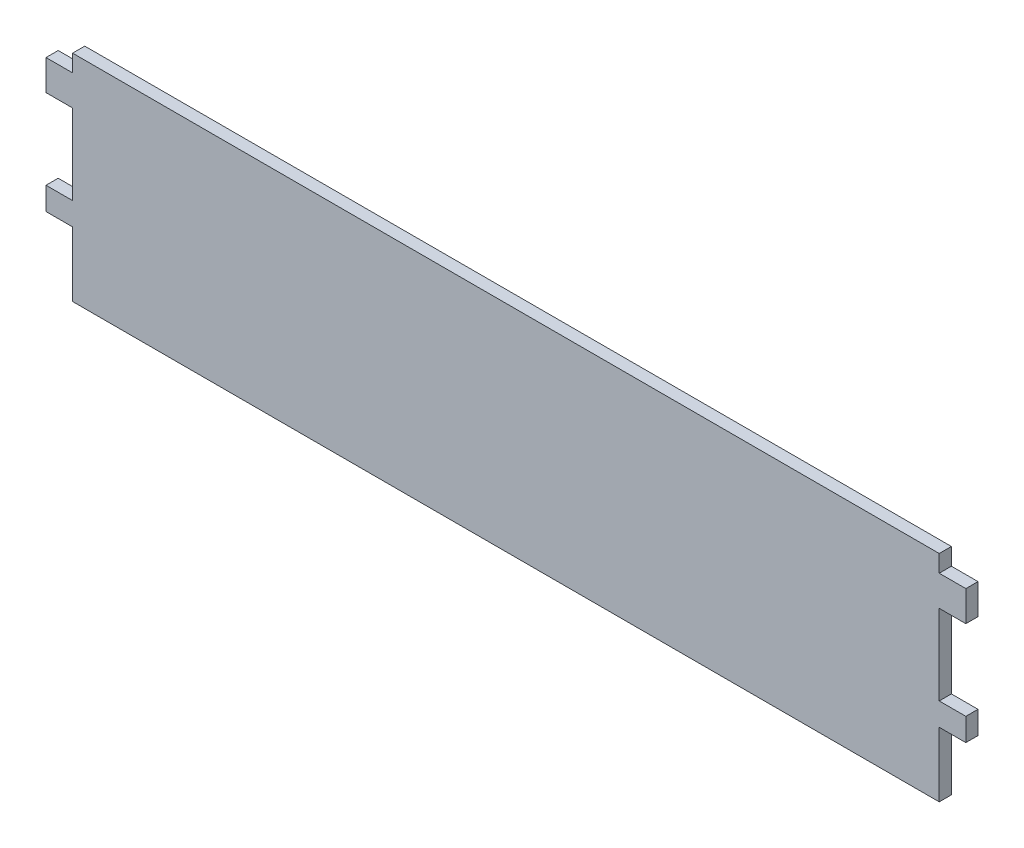
SolidWorks part; units mm, degrees
ref_plane "前视基准面" through (0, 0, 0) normal (0, 0, 1) x (1, 0, 0)
ref_plane "上视基准面" through (0, 0, 0) normal (0, 1, 0) x (1, 0, 0)
ref_plane "右视基准面" through (0, 0, 0) normal (1, 0, 0) x (0, 0, -1)
sketch "草图1" plane through (0, 0, 0) normal (0, 0, 1) x (1, 0, 0)
  line L0 (0, 0) -> (0, 38.8053) construction
  line L11 (0, 0) -> (-51.2518, 0) construction
  line L12 (60.5, 4) -> (-60.5, 4)
  line L13 (-60.5, 4) -> (-60.5, 0)
  line L14 (-60.5, 0) -> (-57, 0)
  line L15 (-57, 0) -> (-57, -13.55) construction
  line L16 (-57, -13.55) -> (57, -13.55)
  line L17 (57, 0) -> (57, -13.55) construction
  line L18 (60.5, 0) -> (57, 0)
  line L19 (60.5, 4) -> (60.5, 0)
  line L20 (-57, -10.55) -> (-60.5, -10.55)
  line L21 (-60.5, -10.55) -> (-60.5, -13.55)
  line L22 (-60.5, -13.55) -> (-57, -13.55)
  line L23 (-57, 0) -> (-57, -10.55)
  line L24 (60.5, -13.55) -> (57, -13.55)
  line L25 (60.5, -10.55) -> (60.5, -13.55)
  line L26 (57, -10.55) -> (60.5, -10.55)
  line L27 (57, 0) -> (57, -10.55)
  line L28 (-60.5, 2) -> (-43.2943, 2) construction
  point P6 (-58.75, 0)
  point P12 (0, -13.55)
  point P15 (0, 4)
  dimension "D1" = 3.5
  dimension "D2" = 4
  dimension "D3" = 114
  dimension "D4" = 12.55
  dimension "D5" = 3
extrude "主体" add sketch "草图1" along normal blind 1.6
ref_plane "旋转轴所在面" through (0, 0, 0.8) normal (0, 0, -1) x (-1, 0, 0)
sketch "旋转轴示意" plane through (0, 0, 0.8) normal (0, 0, -1) x (-1, 0, 0)
  line L0 (-60.5, 2) -> (-89.9569, 2) construction
  line L1 (-60.5, 0) -> (-60.5, 4) construction
sketch "草图3" plane through (0, 0, 0) normal (0, 0, -1) x (-1, 0, 0)
  line L0 (-57, 4) -> (-57, 6.25)
  line L1 (-60.5, 4) -> (60.5, 4) construction
  line L2 (-57, 6.25) -> (57, 6.25)
  line L3 (57, 6.25) -> (57, 4)
  line L4 (57, 4) -> (-57, 4)
  line L5 (-57, -10.55) -> (-57, 0) construction
  line L6 (57, 0) -> (57, -10.55) construction
  line L7 (-57, -22.05) -> (-57, -13.55)
  line L8 (-57, -13.55) -> (57, -13.55)
  line L9 (57, -13.55) -> (57, -22.05)
  line L10 (57, -22.05) -> (-57, -22.05)
  line L11 (60.5, -13.55) -> (-60.5, -13.55) construction
  dimension "D1" = 2.25
  dimension "D2" = 8.5
extrude "结构补强" add sketch "草图3" against normal up to surface (1.6 mm away) up to face at (0, -5.1083, 1.6)
sketch "草图4" plane through (0, 0, 0) normal (0, 0, -1) x (-1, 0, 0)
  line L0 (-60.5, -12.05) -> (60.5, -12.05) construction
  line L1 (-60.5, -13.55) -> (-60.5, -10.55) construction
  line L2 (60.5, -10.55) -> (60.5, -13.55) construction
  text T0 "  厦门大学" font "钟齐志莽行书" height 12.5
extrude "Logo" cut sketch "草图4" along normal through all and the other way blind 1
